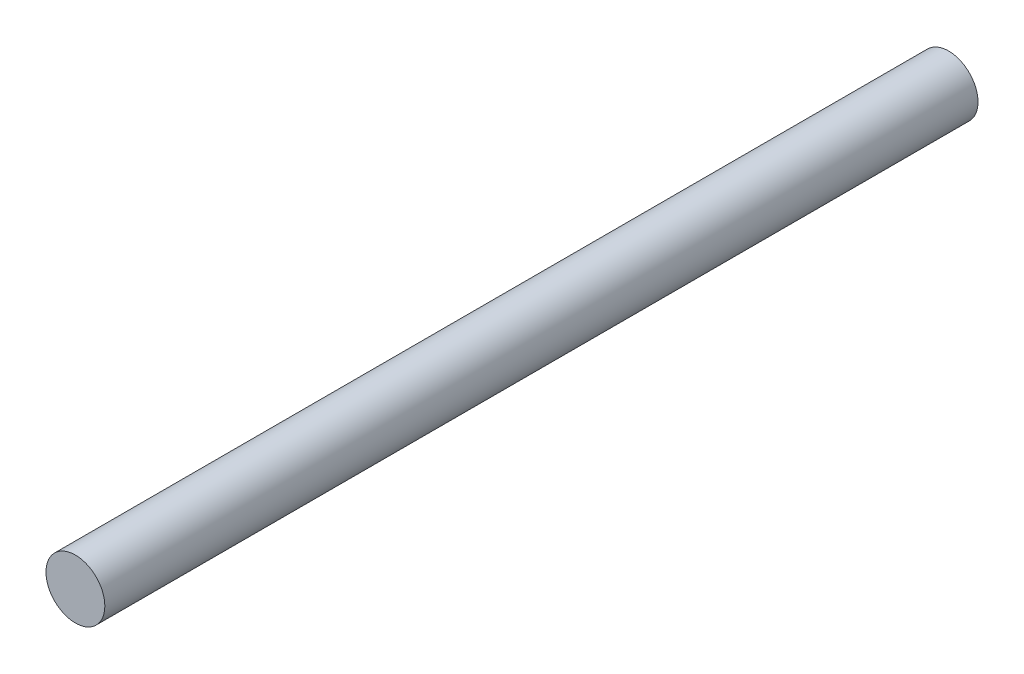
SolidWorks part; units mm, degrees
ref_plane "前视基准面" through (0, 0, 0) normal (0, 0, 1) x (1, 0, 0)
ref_plane "上视基准面" through (0, 0, 0) normal (0, 1, 0) x (1, 0, 0)
ref_plane "右视基准面" through (0, 0, 0) normal (1, 0, 0) x (0, 0, -1)
sketch "草图1" plane through (0, 0, 0) normal (0, 0, 1) x (1, 0, 0)
  circle A0 centre (0, 0) radius 10
extrude "凸台-拉伸1" add sketch "草图1" along normal blind 296.5
